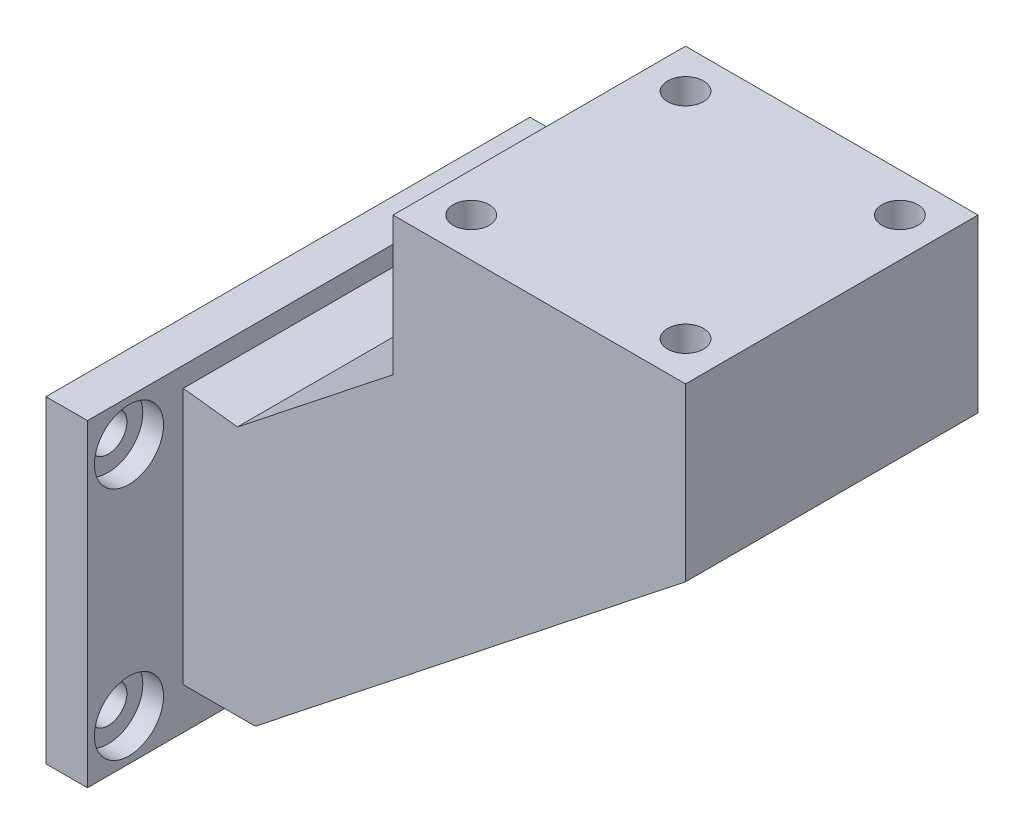
SolidWorks part; units mm, degrees
ref_plane "Piano frontale" through (0, 0, 0) normal (0, 0, 1) x (1, 0, 0)
ref_plane "Piano superiore" through (0, 0, 0) normal (0, 1, 0) x (1, 0, 0)
ref_plane "Piano destro" through (0, 0, 0) normal (1, 0, 0) x (0, 0, -1)
sketch "Schizzo1" plane through (0, 0, 0) normal (0, 0, 1) x (1, 0, 0)
  line L0 (0, 0) -> (0, 46)
  line L1 (0, 46) -> (6, 46)
  line L2 (6, 46) -> (6, 36)
  line L3 (6, 36) -> (36.35, 60)
  line L4 (36.35, 60) -> (36.35, 80)
  line L5 (36.35, 80) -> (78.65, 80)
  line L9 (6, 6) -> (6, 0)
  line L10 (6, 0) -> (0, 0)
  line L11 (78.65, 80) -> (78.65, 55.2033)
  line L12 (78.65, 55.2033) -> (16.4283, 6)
  line L13 (16.4283, 6) -> (6, 6)
  line L14 (6, 36) -> (6, 6) construction
  line L16 (57.5, 80) -> (57.5, 38.4784) construction
  line L17 (4, 46) -> (4, 0) construction
  point P10 (3, 0)
  dimension "D1" = 42.3
  dimension "D2" = 6
  dimension "D3" = 4
  dimension "D4" = 80
  dimension "D5" = 30
  dimension "D6" = 46
  dimension "D7" = 30
  dimension "D8" = 53.5
  dimension "D9" = 20
  dimension "D10" = 10
extrude "Estrusione-Estrusione1" add sketch "Schizzo1" along normal blind 70
sketch "Schizzo2" plane through (0, 46, 0) normal (0, 1, 0) x (1, 0, 0)
  line L1 (0, -35) -> (-106.5, -35) construction
  line L2 (0, -70) -> (0, 0) construction
  line L5 (4, 0) -> (4, -70) construction
  line L6 (6, 0) -> (0, 0) construction
  line L7 (6, -70) -> (0, -70) construction
  circle A0 centre (-106.5, -35) radius 110.5
  dimension "D1" = 221
  dimension "D2" = 4
extrude "Taglio-Estrusione1" [suppressed] cut sketch "Schizzo2" against normal blind 50
sketch "Schizzo3" plane through (0, 0, 70) normal (0, 0, 1) x (1, 0, 0)
  line L0 (6, 36) -> (36.35, 60)
  line L1 (36.35, 60) -> (36.35, 80)
  line L2 (36.35, 80) -> (52.7857, 80)
  line L3 (78.65, 80) -> (36.35, 80) construction
  line L4 (78.65, 80) -> (78.65, 55.2033)
  line L5 (78.65, 55.2033) -> (16.4283, 6)
  line L6 (16.4283, 6) -> (6, 6)
  line L7 (6, 6) -> (6, 36)
  line M3 (6, 6) -> (16.4283, 6)
  line M4 (16.4283, 6) -> (78.65, 55.2033)
  line M5 (78.65, 55.2033) -> (78.65, 80)
  line M6 (78.65, 80) -> (36.35, 80)
  line M7 (36.35, 80) -> (36.35, 60)
  line M8 (36.35, 60) -> (6, 36)
extrude "Taglio-Estrusione2" cut sketch "Schizzo3" against normal blind 13.85 and the other way through all contours L7 M3 M4 M5 M6 M7 M8
sketch "Schizzo4" plane through (0, 0, 0) normal (0, 0, -1) x (-1, 0, 0)
  line L0 (-36.35, 60) -> (-36.35, 80)
  line L1 (-36.35, 80) -> (-78.65, 80)
  line L2 (-78.65, 80) -> (-78.65, 55.2033)
  line L4 (-78.65, 55.2033) -> (-16.4283, 6)
  line L5 (-16.4283, 6) -> (-6, 6)
  line L6 (-6, 6) -> (-6, 36)
  line L7 (-6, 36) -> (-36.35, 60)
extrude "Taglio-Estrusione3" cut sketch "Schizzo4" against normal blind 13.85
sketch "Schizzo5" plane through (36.35, 0, 0) normal (-1, 0, 0) x (0, 0, 1)
  line L0 (13.85, 60) -> (13.85, 80) construction
  line L1 (15.35, 78.5) -> (54.65, 78.5)
  line L2 (15.35, 78.5) -> (15.35, 61.5)
  line L3 (15.35, 61.5) -> (54.65, 61.5)
  line L4 (54.65, 78.5) -> (54.65, 61.5)
  line L5 (56.15, 80) -> (13.85, 80) construction
  line L6 (56.15, 80) -> (56.15, 60) construction
  line L7 (56.15, 60) -> (13.85, 60) construction
  dimension "D1" = 1.5
  dimension "D2" = 1.5
  dimension "D3" = 1.5
  dimension "D4" = 1.5
extrude "Taglio-Estrusione4" [suppressed] cut sketch "Schizzo5" against normal blind 40.8
hole_wizard "Foro lamato per Bullone M12 a testa esagonale (Classe superiore)-1" positions "Schizzo6" profile "Schizzo7" counterbore size "M12" standard "DIN"
sketch "Schizzo6" plane through (6, 0, 0) normal (1, 0, 0) x (0, 0, -1)
  line L1 (-64, 40) -> (-6, 40) construction
  line L2 (-64, 40) -> (-64, 6) construction
  line L3 (-64, 6) -> (-6, 6) construction
  line L4 (-6, 40) -> (-6, 6) construction
  line L5 (-70, 0) -> (-70, 46) construction
  line L6 (-70, 46) -> (0, 46) construction
  line L7 (-70, 0) -> (0, 0) construction
  line L8 (0, 0) -> (0, 46) construction
  point P0 (-64, 6)
  point P2 (-6, 6)
  point P4 (-6, 40)
  point P6 (-64, 40)
  dimension "D1" = 6
  dimension "D2" = 6
  dimension "D3" = 6
  dimension "D4" = 6
sketch "Schizzo7" plane through (6, 6, 64) normal (0, 1, 0) x (0, 0, -1)
  line L0 (0, 0) -> (0, 19.7223)
  line L1 (0, 19.7223) -> (2.7, 18.1)
  line L2 (2.7, 18.1) -> (2.7, 3)
  line L3 (2.7, 3) -> (5, 3)
  line L4 (5, 3) -> (5, 0)
  line L5 (5, 0) -> (0, 0)
  line L10 (0, 19.7223) -> (-2.7, 18.1) construction
  line L11 (0, -6.35) -> (0, 107.95) construction
  dimension "Hole Dia." = 5.4
  dimension "Hole Depth" = 18.1
  dimension "C'Bore Dia." = 10
  dimension "C'Bore Depth" = 3
  dimension "Drill Angle" = 118
chamfer "Smusso1" distance 10 angle 45 1 edges at (6, 36, 35)
sketch "Schizzo9" plane through (0, 80, 0) normal (0, 1, 0) x (1, 0, 0)
  line L1 (42, -19.5) -> (73, -19.5)
  line L2 (42, -19.5) -> (42, -50.5)
  line L3 (42, -50.5) -> (73, -50.5)
  line L4 (73, -19.5) -> (73, -50.5)
  line L5 (36.35, -13.85) -> (78.65, -56.15) construction
  line L7 (36.35, -56.15) -> (78.65, -13.85) construction
  point P0 (42, -19.5)
  point P2 (73, -19.5)
  point P4 (73, -50.5)
  point P6 (42, -50.5)
  point P140 (0, 0)
  point P141 (0, 0)
  dimension "D1" = 31
hole_wizard "Foro per Vite M4-1" positions "Schizzo9" profile "Schizzo10" hole size "M4" standard "DIN"
sketch "Schizzo10" plane through (42, 80, 19.5) normal (1, 0, 0) x (0, 0, 1)
  line L0 (0, 0) -> (0, 9.6622)
  line L1 (0, 9.6622) -> (2.6, 8.1)
  line L2 (2.6, 8.1) -> (2.6, 0)
  line L5 (2.6, 0) -> (0, 0)
  line L10 (0, 9.6622) -> (-2.6, 8.1) construction
  line L11 (0, -6.35) -> (0, 107.95) construction
  dimension "Hole Dia." = 5.2
  dimension "Hole Depth" = 8.1
  dimension "Drill Angle" = 118
